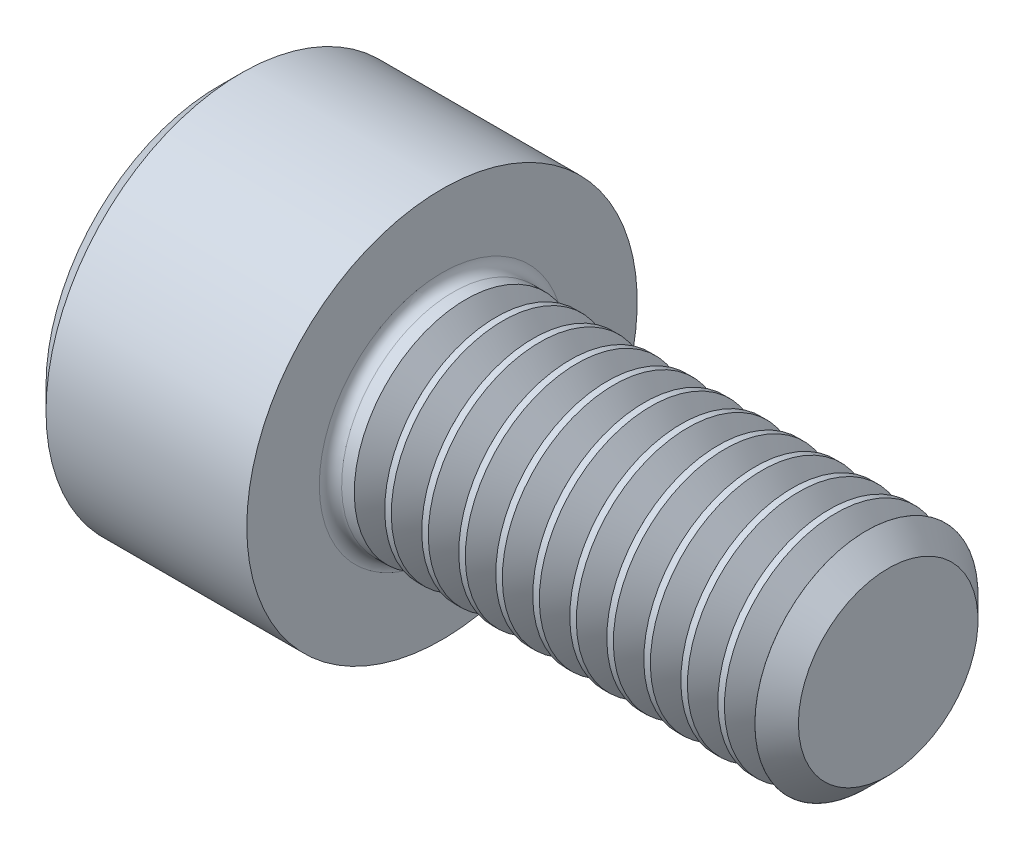
SolidWorks part; units mm, degrees
revolve "Base-Revolve" add sketch "BodySke"
sketch "BodySke" plane through (0, 0, 0) normal (0, 0, 1) x (1, 0, 0)
  line L0 (0, 0) -> (0, 3.1)
  line L1 (0.4, 3.5) -> (4, 3.5)
  line L2 (4, 3.5) -> (4, 2)
  line L3 (4, 2) -> (11.61, 2)
  line L4 (12, 1.61) -> (12, 0)
  line L5 (12, 0) -> (0, 0)
  line L6 (-31.75, 0) -> (127, 0) construction
  line L7 (0, 3.1) -> (0.4, 3.5)
  line L8 (12, 1.61) -> (11.61, 2)
  line L9 (0, -3.1) -> (0.4, -3.5) construction
  line L10 (12, -1.61) -> (11.61, -2) construction
  line L11 (4.7, 9.525) -> (4.7, 3.175) construction
  line L12 (4, 9.525) -> (4, 3.175) construction
  line L13 (-38, 9.525) -> (-38, 3.175) construction
  dimension "Diameter" = 4
  dimension "Head_ht" = 4
  dimension "Length" = 8
  dimension "Body_ch_ang" = 45
  dimension "Head_dia" = 7
  dimension "Head_ch_ang" = 45
  dimension "Minor_dia" = 3.22
  dimension "Advance" = 0.7
  dimension "Thread_nom" = 8
  dimension "Thread_length" = 50
  dimension "Head_ch_ht" = 0.4
cosmetic thread "ThreadCosmetic" [suppressed]
fillet "Fillet1" radius 0.2 1 edges at (4, 0, 2)
ref_plane "Plane1" through (0, 0, 0) normal (0, 0, 1) x (1, 0, 0)
ref_plane "Plane2" through (0, 0, 0) normal (0, 1, 0) x (1, 0, 0)
ref_plane "Plane3" through (0, 0, 0) normal (1, 0, 0) x (0, 0, -1)
sketch "Sketch2" plane through (0, 0, 0) normal (0, 0, 1) x (1, 0, 0)
  line L0 (0, 1.5355) -> (2, 1.5355)
  line L1 (2, 1.5355) -> (2.8865, 0)
  line L2 (-31.75, 0) -> (127, 0) construction
  line L3 (2.8865, 0) -> (0, 0)
  line L4 (0, 0) -> (0, 1.5355)
  line L5 (0, 3.1) -> (0, -3.1) construction
  line L6 (0, 0) -> (47.625, 0) construction
  line L7 (4, -3.5) -> (4, 3.5) construction
  dimension "D1" = 1.5355
  dimension "D2" = 60
revolve "Hex-PreBroach" cut sketch "Sketch2" angle 360 about L6
sketch "Sketch3" plane through (0, 0, 0) normal (-1, 0, 0) x (0, 0.5, 0.866)
  line L0 (0.8865, 1.5355) -> (-0.8865, 1.5355)
  line L1 (-0.8865, 1.5355) -> (-1.773, 0)
  line L2 (0.8865, 1.5355) -> (1.773, 0)
  line L3 (0.8865, -1.5355) -> (1.773, 0)
  line L4 (0.8865, -1.5355) -> (-0.8865, -1.5355)
  line L5 (-0.8865, -1.5355) -> (-1.773, 0)
  dimension "D1" = 1.5355
  dimension "D2" = 1.5355
  dimension "Hex_size" = 3.071
extrude "Hex" cut sketch "Sketch3" against normal blind 2
sketch "Sketch4" plane through (0, 0, 0) normal (-1, 0, 0) x (0, 0, 1)
  line L0 (0, 0) -> (1.7399, 0)
  line L1 (0, 0) -> (6.1484, 3.5498) construction
  line L2 (0, 0) -> (0.8699, 1.5068)
  line L3 (1.4457, 0.3947) -> (1.6607, 0.5189)
  line L4 (1.0647, 1.0546) -> (1.2797, 1.1788)
  arc A0 (1.4457, 0.3947) -> (1.0647, 1.0546) centre (0, 0) ccw
  arc A1 (1.7399, 0) -> (1.6607, 0.5189) centre (0, 0) ccw
  arc A2 (0.8699, 1.5068) -> (1.2797, 1.1788) centre (0, 0) cw
  dimension "D1" = 30
  dimension "D2" = 60
  dimension "Spline_p_dim" = 0.762
  dimension "D3" = 0.381
extrude "Spline" [suppressed] cut sketch "Sketch4" against normal blind 2
pattern_circular "CirPattern1" [suppressed] count 6 every 60
sketch "Sketch5" plane through (0, 0, 0) normal (0, 0, 1) x (1, 0, 0)
  line L0 (-31.75, 0) -> (127, 0) construction
  line L2 (0, 3.1) -> (0, -3.1) construction
  circle A0 centre (1.6, 0) radius 0.675
  dimension "Drilled_hole_dia" = 1.35
  dimension "Drilled_hole_loc" = 1.6
extrude "Hole" [suppressed] cut sketch "Sketch5" against normal through all and the other way through all
pattern_circular "Drilled-4" [suppressed] count 2 every 60
pattern_circular "Drilled-6" [suppressed] count 3 every 60
sketch "ThdSchSke" plane through (0, 0, 0) normal (0, 0, 1) x (1, 0, 0)
  line L0 (4.7, -1.61) -> (4.4269, -2)
  line L1 (4.7, -1.61) -> (4.9731, -2)
  line L2 (4.9731, -2) -> (4.9731, -2.5)
  line L3 (-3.175, 0) -> (5.1513, 0) construction
  line L5 (4.9731, -2.5) -> (4.4269, -2.5)
  line L6 (4.4269, -2.5) -> (4.4269, -2)
  line L7 (0, 3.1) -> (0, -3.1) construction
  dimension "Thread_minor" = 3.22
  dimension "Diameter" = 4
  dimension "Start" = 4.7
revolve "ThreadSchematic" cut sketch "ThdSchSke" angle 360 about L3
pattern_linear "ThdSchPat" count 11 spacing 0.6636 along (1, 0, 0) of "ThreadSchematic"
move or copy body "Body-Move/Copy1" [suppressed] bodies to move or copy 106
equation "\"D2@Sketch3\" = \"Hex_size@Sketch3\" / 2"
equation "\"D1@Sketch3\" = \"Hex_size@Sketch3\" / 2"
equation "\"D1@Sketch2\" = \"Hex_size@Sketch3\" / 2"
equation "\"D3@Sketch4\" = \"Spline_p_dim@Sketch4\" / 2"
equation "\"Thread_minor@ThreadCosmetic\"  =  \"Minor_dia@BodySke\""
equation "\"D2@CirPattern1\" = 360 / \"Num_teeth@CirPattern1\""
equation "\"Wall_thickness@Sketch2\" = \"Head_ht@BodySke\" - \"Key_eng@Hex\""
equation "\"Thread_length@ThreadCosmetic\" = ((sgn( (\"Length@BodySke\" - \"Advance@BodySke\" ) - \"Thread_nom@BodySke\" )-1)*( (\"Length@BodySke\" - \"Advance@BodySke\" ) - \"Thread_nom@BodySke\" ))/-2+ \"Thread_nom@BodySke\""
equation "\"Thread_minor@ThdSchSke\" = \"Minor_dia@BodySke\""
equation "\"Diameter@ThdSchSke\" = \"Diameter@BodySke\""
equation "\"Overcut@ThdSchSke\" = \"Diameter@BodySke\" * 1.25"
equation "\"Start@ThdSchSke\" = \"Head_ht@BodySke\" + \"Length@BodySke\" - \"Thread_length@ThreadCosmetic\"  '---Non-countersunk---"
equation "\"Num_threads@ThdSchPat\" = int( \"Thread_length@ThreadCosmetic\" / \"Advance@BodySke\" + 0.999 )  + 1"
equation "\"Advance@ThdSchPat\" = \"Thread_length@ThreadCosmetic\" /  (\"Num_threads@ThdSchPat\" - 1) 'relax it"
equation "\"Num_threads@ThdSchPat\" = \"Num_threads@ThdSchPat\" - sgn( \"Num_threads@ThdSchPat\" - 1) '---chamfered tips only---"
